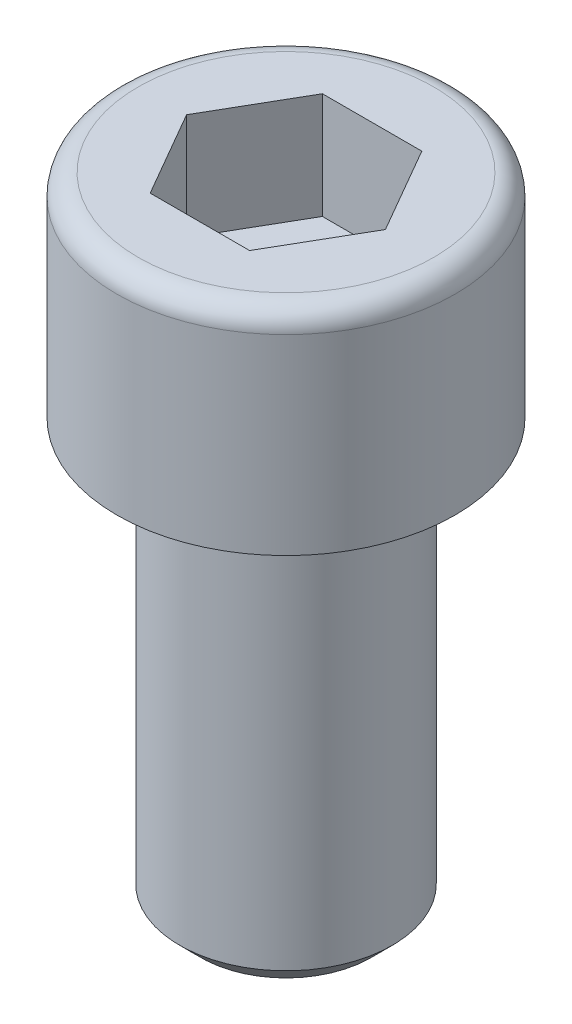
SolidWorks part; units mm, degrees
ref_plane "Plan de face" through (0, 0, 0) normal (0, 0, 1) x (1, 0, 0)
ref_plane "Plan de dessus" through (0, 0, 0) normal (0, 1, 0) x (1, 0, 0)
ref_plane "Plan de droite" through (0, 0, 0) normal (1, 0, 0) x (0, 0, -1)
sketch "Esquisse1" plane through (0, 0, 0) normal (0, 0, 1) x (1, 0, 0)
  line L0 (7.95, 10) -> (0, 10)
  line L1 (0, 10) -> (0, 0)
  line L2 (0, 0) -> (7.95, 0)
  line L3 (7.95, 0) -> (7.95, 10)
  line L4 (0, 10) -> (0, 0) construction
revolve "Révolution1" add sketch "Esquisse1" angle 360 about L4
sketch "Esquisse2" plane through (0, 0, 0) normal (0, -1, 0) x (1, 0, 0)
  circle A0 centre (0, 0) radius 5
extrude "Boss.-Extru.1" add sketch "Esquisse2" along normal blind 20
sketch "Esquisse3" plane through (0, 10, 0) normal (0, 1, 0) x (-1, 0, 0)
  line L0 (2.3383, 4.05) -> (-2.3383, 4.05)
  line L1 (-2.3383, 4.05) -> (-4.6765, 0)
  line L2 (-4.6765, 0) -> (-2.3383, -4.05)
  line L3 (-2.3383, -4.05) -> (2.3383, -4.05)
  line L4 (2.3383, -4.05) -> (4.6765, 0)
  line L5 (4.6765, 0) -> (2.3383, 4.05)
extrude "Enlèv. mat.-Extru.1" cut sketch "Esquisse3" against normal blind 5
chamfer "Chanfrein1" distance 1 angle 45 1 edges at (0, -20, -5)
fillet "Congé1" radius 1 1 edges at (0, 10, -7.95)
